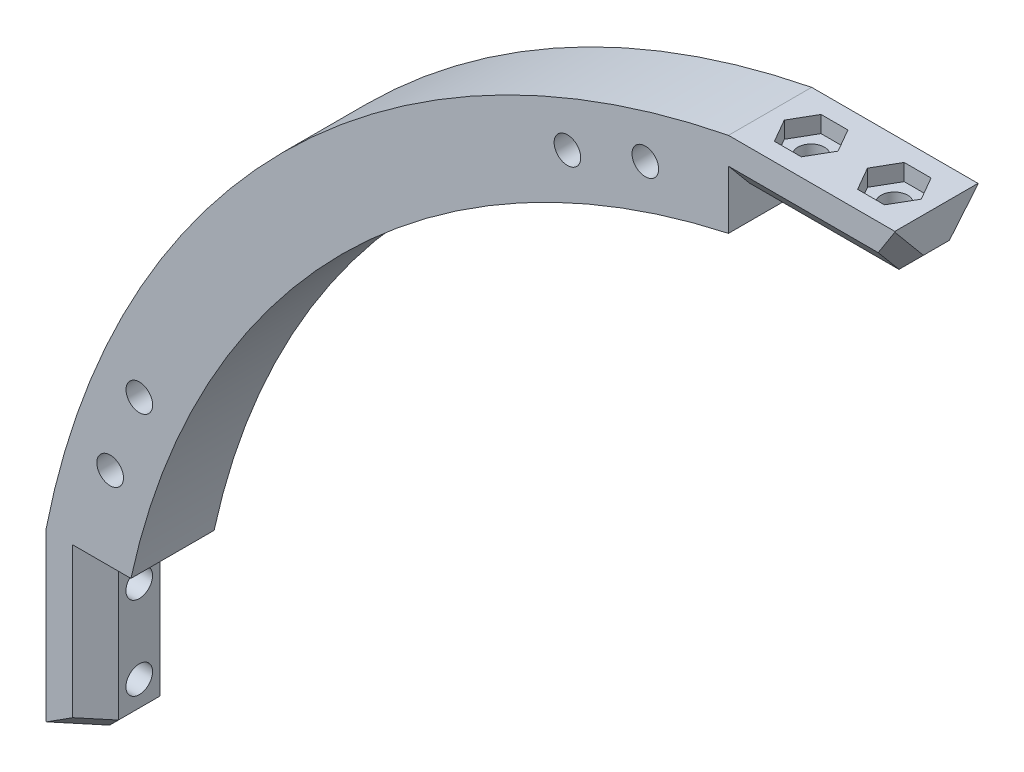
SolidWorks part; units mm, degrees
ref_plane "Plan de face" through (0, 0, 0) normal (0, 0, 1) x (1, 0, 0)
ref_plane "Plan de dessus" through (0, 0, 0) normal (0, 1, 0) x (1, 0, 0)
ref_plane "Plan de droite" through (0, 0, 0) normal (1, 0, 0) x (0, 0, -1)
sketch "Esquisse1" plane through (0, 0, 0) normal (0, 0, 1) x (1, 0, 0)
  line L0 (0, 20) -> (-56.711, 20) construction
  line L1 (-20, 8.5699) -> (-20, 91.8477) construction
  line L5 (-20, 102.0588) -> (0, 102.0588)
  line L7 (-20, 91.8477) -> (0, 91.8477)
  line L8 (0, 102.0588) -> (0, 91.8477)
  line L10 (-91.8477, 20) -> (-91.8477, 0)
  line L11 (-91.8477, 0) -> (-102.0588, 0)
  line L12 (-102.0588, 20) -> (-102.0588, 0)
  arc A0 (-20, 91.8477) -> (-91.8477, 20) centre (0, 0) ccw
  arc A1 (-20, 102.0588) -> (-102.0588, 20) centre (0, 0) ccw
  dimension "D1" = 188
  dimension "D2" = 10
  dimension "D3" = 20
  dimension "D4" = 20
  dimension "D5" = 20
  dimension "D6" = 20
extrude "Boss.-Extru.1" add sketch "Esquisse1" along normal blind 10 contours A1 L12 L11 L10 A0 L7 L8 L5
sketch "Esquisse2" plane through (0, 0, 0) normal (0, -1, 0) x (1, 0, 0)
  line L0 (-98.8477, 10) -> (-91.8477, 10)
  line L1 (-91.8477, 10) -> (-102.0588, 10) construction
  line L2 (-91.8477, 10) -> (-91.8477, 0)
  line L3 (-91.8477, 0) -> (-98.8477, 0)
  line L4 (-91.8477, 0) -> (-102.0588, 0) construction
  line L5 (-98.8477, 0) -> (-95.8477, 2.5)
  line L6 (-95.8477, 2.5) -> (-95.8477, 7.5)
  line L7 (-95.8477, 7.5) -> (-98.8477, 10)
  dimension "D1" = 7
  dimension "D2" = 7
  dimension "D3" = 4
  dimension "D4" = 5
  dimension "D5" = 2.5
extrude "Enlèv. mat.-Extru.1" cut sketch "Esquisse2" against normal blind 20
sketch "Esquisse4" plane through (0, 0, 0) normal (1, 0, 0) x (0, 0, -1)
  line L0 (0, 98.8477) -> (0, 91.8477)
  line L1 (0, 102.0588) -> (0, 91.8477) construction
  line L2 (0, 91.8477) -> (-10, 91.8477)
  line L3 (-10, 91.8477) -> (-10, 98.8477)
  line L4 (-10, 102.0588) -> (-10, 91.8477) construction
  line L5 (-10, 98.8477) -> (-7.5, 95.8477)
  line L6 (-7.5, 95.8477) -> (-2.5, 95.8477)
  line L7 (-2.5, 95.8477) -> (0, 98.8477)
  dimension "D1" = 7
  dimension "D2" = 7
  dimension "D3" = 5
  dimension "D4" = 2.5
  dimension "D5" = 4
extrude "Enlèv. mat.-Extru.2" cut sketch "Esquisse4" against normal blind 20
sketch "Esquisse5" plane through (-95.8477, 0, 0) normal (1, 0, 0) x (0, 0, -1)
  line L0 (-10, 20) -> (-10, 0) construction
  line L1 (-7.5, 0) -> (-2.5, 0) construction
  circle A0 centre (-5, 5) radius 1.6
  circle A1 centre (-5, 15) radius 1.6
  dimension "D1" = 3.2
  dimension "D2" = 3.2
  dimension "D3" = 5
  dimension "D4" = 5
  dimension "D5" = 5
  dimension "D6" = 10
extrude "Enlèv. mat.-Extru.3" cut sketch "Esquisse5" against normal blind 20
sketch "Esquisse6" plane through (0, 95.8477, 0) normal (0, -1, 0) x (1, 0, 0)
  line L0 (0, 2.5) -> (0, 7.5) construction
  circle A0 centre (-5, 5.059) radius 1.6
  circle A1 centre (-15, 5.059) radius 1.6
  dimension "D1" = 3.2
  dimension "D2" = 3.2
  dimension "D3" = 5
  dimension "D4" = 10
extrude "Enlèv. mat.-Extru.4" cut sketch "Esquisse6" against normal blind 20
chamfer "Chanfrein1" distance 2 angle 45 6 edges at (-97.3477, 0, 1.25) (-95.8477, 0, 5) (-97.3477, 0, 8.75) (0, 97.3477, 1.25) (0, 97.3477, 8.75) (0, 95.8477, 5)
sketch "Esquisse7" plane through (-102.0588, 0, 0) normal (-1, 0, 0) x (0, 0, 1)
  line L0 (10, 0) -> (0, 0) construction
  line L1 (2.2, 6.6166) -> (2.2, 3.3834)
  line L2 (2.2, 3.3834) -> (5, 1.7668)
  line L3 (5, 1.7668) -> (7.8, 3.3834)
  line L4 (7.8, 3.3834) -> (7.8, 6.6166)
  line L5 (7.8, 6.6166) -> (5, 8.2332)
  line L6 (5, 8.2332) -> (2.2, 6.6166)
  line L7 (7.8, 16.6166) -> (5, 18.2332)
  line L8 (5, 18.2332) -> (2.2, 16.6166)
  line L9 (2.2, 16.6166) -> (2.2, 13.3834)
  line L10 (2.2, 13.3834) -> (5, 11.7668)
  line L11 (5, 11.7668) -> (7.8, 13.3834)
  line L12 (7.8, 13.3834) -> (7.8, 16.6166)
  circle A0 centre (5, 5) radius 2.8 construction
  circle A1 centre (5, 15) radius 2.8 construction
  dimension "D1" = 5.6
  dimension "D2" = 5.6
  dimension "D3" = 90
  dimension "D4" = 90
extrude "Enlèv. mat.-Extru.5" cut sketch "Esquisse7" against normal blind 2
sketch "Esquisse8" plane through (0, 102.0588, 0) normal (0, 1, 0) x (1, 0, 0)
  line L0 (0, -10) -> (0, 0) construction
  line L1 (-3.3834, -2.259) -> (-6.6166, -2.259)
  line L2 (-6.6166, -2.259) -> (-8.2332, -5.059)
  line L3 (-8.2332, -5.059) -> (-6.6166, -7.859)
  line L4 (-6.6166, -7.859) -> (-3.3834, -7.859)
  line L5 (-3.3834, -7.859) -> (-1.7668, -5.059)
  line L6 (-1.7668, -5.059) -> (-3.3834, -2.259)
  line L8 (-13.3834, -2.259) -> (-16.6166, -2.259)
  line L9 (-16.6166, -2.259) -> (-18.2332, -5.059)
  line L10 (-18.2332, -5.059) -> (-16.6166, -7.859)
  line L11 (-16.6166, -7.859) -> (-13.3834, -7.859)
  line L12 (-13.3834, -7.859) -> (-11.7668, -5.059)
  line L13 (-11.7668, -5.059) -> (-13.3834, -2.259)
  circle A0 centre (-5, -5.059) radius 2.8 construction
  circle A1 centre (-15, -5.059) radius 2.8 construction
  dimension "D1" = 90
  dimension "D2" = 90
  dimension "D3" = 5.6
  dimension "D4" = 5.6
extrude "Enlèv. mat.-Extru.6" cut sketch "Esquisse8" against normal blind 2
sketch "Esquisse9" plane through (0, 0, 0) normal (0, 0, -1) x (-1, 0, 0)
  line L1 (98.8477, 20) -> (91.8477, 20) construction
  line L2 (20, 91.8477) -> (20, 98.8477) construction
  circle A0 centre (94.3451, 30) radius 1.6
  circle A1 centre (90.8374, 39.3646) radius 1.6
  arc A2 (91.8477, 20) -> (20, 91.8477) centre (0, 0) ccw construction
  circle A3 centre (30, 94.3451) radius 1.6
  circle A4 centre (39.3646, 90.8374) radius 1.6
  arc A5 (91.8477, 20) -> (20, 91.8477) centre (0, 0) ccw construction
  dimension "D3" = 3.2
  dimension "D4" = 3.2
  dimension "D7" = 3.2
  dimension "D8" = 3.2
  dimension "D1" = 99
  dimension "D2" = 99
  dimension "D5" = 10
  dimension "D6" = 10
  dimension "D9" = 99
  dimension "D10" = 99
  dimension "D11" = 10
  dimension "D12" = 10
extrude "Enlèv. mat.-Extru.7" cut sketch "Esquisse9" against normal blind 10
